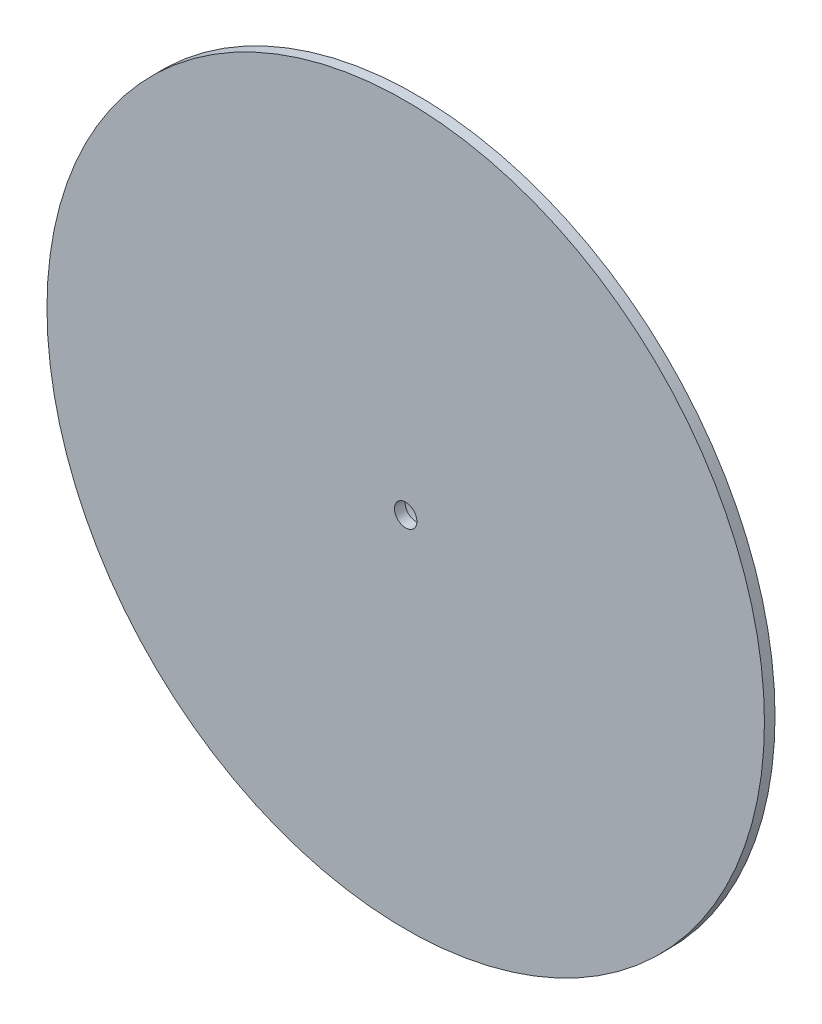
SolidWorks part; units mm, degrees
material "VeroWhite Plus"
ref_plane "Front Plane" through (0, 0, 0) normal (0, 0, 1) x (1, 0, 0)
ref_plane "Top Plane" through (0, 0, 0) normal (0, 1, 0) x (1, 0, 0)
ref_plane "Right Plane" through (0, 0, 0) normal (1, 0, 0) x (0, 0, -1)
sketch "Sketch1" plane through (0, 0, 0) normal (0, 0, 1) x (1, 0, 0)
  circle A0 centre (0, 0) radius 2.6
  circle A1 centre (0, 0) radius 9.525
  dimension "D1" = 5.2
  dimension "D2" = 19.05
extrude "Boss-Extrude1" add sketch "Sketch1" along normal blind 5
sketch "Sketch2" plane through (0, 0, 5) normal (0, 0, 1) x (1, 0, 0)
  circle A0 centre (0, 0) radius 25.4
  dimension "D1" = 50.8
extrude "Boss-Extrude2" add sketch "Sketch2" along normal blind 0.75
ref_plane "Plane1" through (0, 9.525, 0) normal (0, 1, 0) x (1, 0, 0)
sketch "Sketch4" plane through (0, 9.525, 0) normal (0, 1, 0) x (1, 0, 0)
  line L0 (2.6, 0) -> (-2.6, 0) construction
  line L1 (2.6, 0) -> (-2.6, 0) construction
  line L2 (9.525, -5) -> (-9.525, -5) construction
  line L3 (9.525, -5) -> (-9.525, -5) construction
  line L4 (0, 0) -> (0, -5) construction
  line L6 (3.7816, -3.525) -> (1.8908, -0.25)
  line L7 (1.8908, -0.25) -> (-1.8908, -0.25)
  line L8 (-1.8908, -0.25) -> (-3.7816, -3.525)
  line L9 (-3.7816, -3.525) -> (-1.8908, -6.8)
  line L10 (-1.8908, -6.8) -> (1.8908, -6.8)
  line L11 (1.8908, -6.8) -> (3.7816, -3.525)
  circle A1 centre (0, -3.525) radius 3.275 construction
  dimension "D1" = 6.55
  dimension "D2" = 0.5
sketch "Sketch6" plane through (0, 0, 5.75) normal (0, 0, 1) x (1, 0, 0)
  circle A0 centre (0, 0) radius 0.7937
  dimension "D1" = 1.5875
extrude "Cut-Extrude2" cut sketch "Sketch6" against normal blind 2.54
sketch "Sketch7" plane through (0, 9.525, 0) normal (0, 1, 0) x (1, 0, 0)
  line L0 (0, 0) -> (0, -5) construction
  line L1 (0, 0) -> (0, -5) construction
  circle A0 centre (0, -2.5) radius 1.4
  dimension "D1" = 2.8
extrude "Cut-Extrude3" cut sketch "Sketch7" against normal up to next
